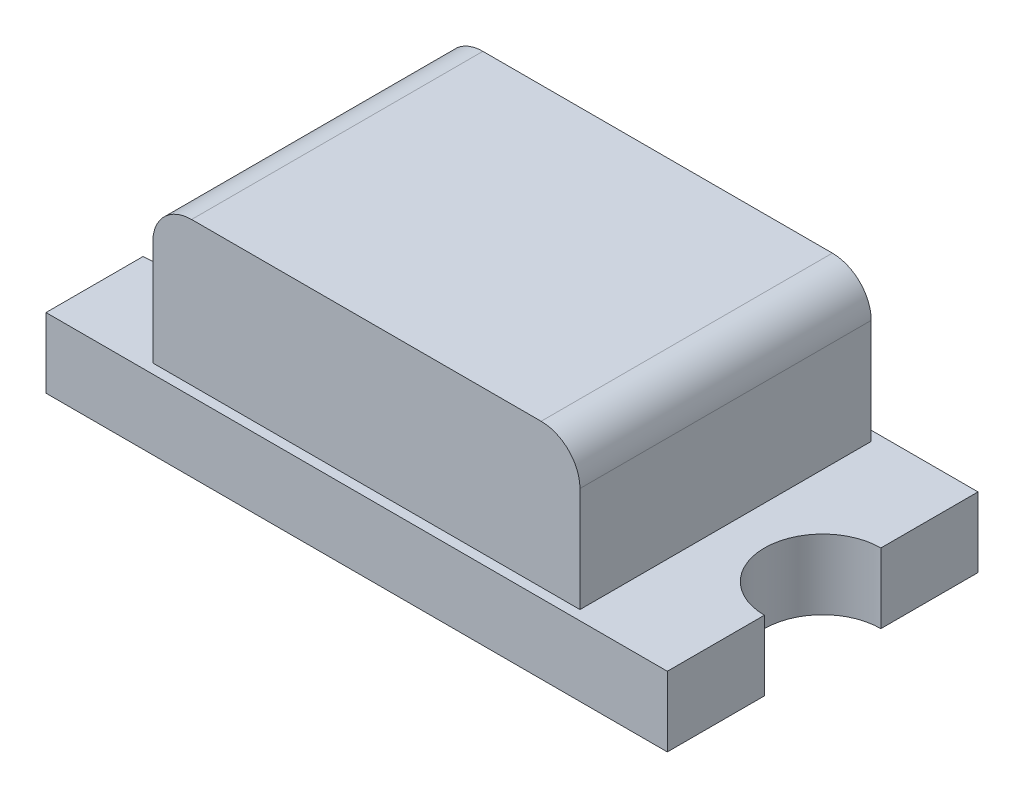
SolidWorks part; units mm, degrees
ref_plane "Front" through (0, 0, 0) normal (0, 0, 1) x (1, 0, 0)
ref_plane "Top" through (0, 0, 0) normal (0, 1, 0) x (1, 0, 0)
ref_plane "Right" through (0, 0, 0) normal (1, 0, 0) x (0, 0, -1)
sketch "Sketch1" plane through (0, 0, 0) normal (0, 1, 0) x (1, 0, 0)
  line L1 (-0.8, -0.4) -> (0.8, -0.4)
  line L2 (-0.8, -0.4) -> (-0.8, 0.4)
  line L3 (-0.8, 0.4) -> (0.8, 0.4)
  line L4 (0.8, -0.4) -> (0.8, 0.4)
  line L5 (-0.8, -0.4) -> (0.8, 0.4) construction
  line L6 (-0.8, 0.4) -> (0.8, -0.4) construction
  point P0 (0, 0)
  dimension "D1" = 0.8
  dimension "D2" = 1.6
extrude "Boss-Extrude1" add sketch "Sketch1" along normal blind 0.18
sketch "Sketch2" plane through (0, 0.18, 0) normal (0, 1, 0) x (1, 0, 0)
  line L0 (-0.8, 0.4) -> (-0.8, -0.4) construction
  line L1 (-0.8, -0.15) -> (-0.8, 0.15)
  arc A0 (-0.8, 0.15) -> (-0.8, -0.15) centre (-0.8, 0) cw
  dimension "D1" = 0.3
extrude "Cut-Extrude1" cut sketch "Sketch2" against normal blind 0.18
mirror "Mirror1" about plane through (0, 0, 0) normal (1, 0, 0) of "Cut-Extrude1"
sketch "Sketch3" plane through (0, 0.18, 0) normal (0, 1, 0) x (1, 0, 0)
  line L1 (-0.55, -0.375) -> (0.55, -0.375)
  line L2 (-0.55, -0.375) -> (-0.55, 0.375)
  line L3 (-0.55, 0.375) -> (0.55, 0.375)
  line L4 (0.55, -0.375) -> (0.55, 0.375)
  line L5 (-0.55, -0.375) -> (0.55, 0.375) construction
  line L6 (-0.55, 0.375) -> (0.55, -0.375) construction
  point P0 (0, 0)
  dimension "D1" = 1.1
  dimension "D2" = 0.75
extrude "Boss-Extrude2" add sketch "Sketch3" along normal blind 0.37
fillet "Fillet1" radius 0.1 2 edges at (0.55, 0.55, 0) (-0.55, 0.55, 0)
